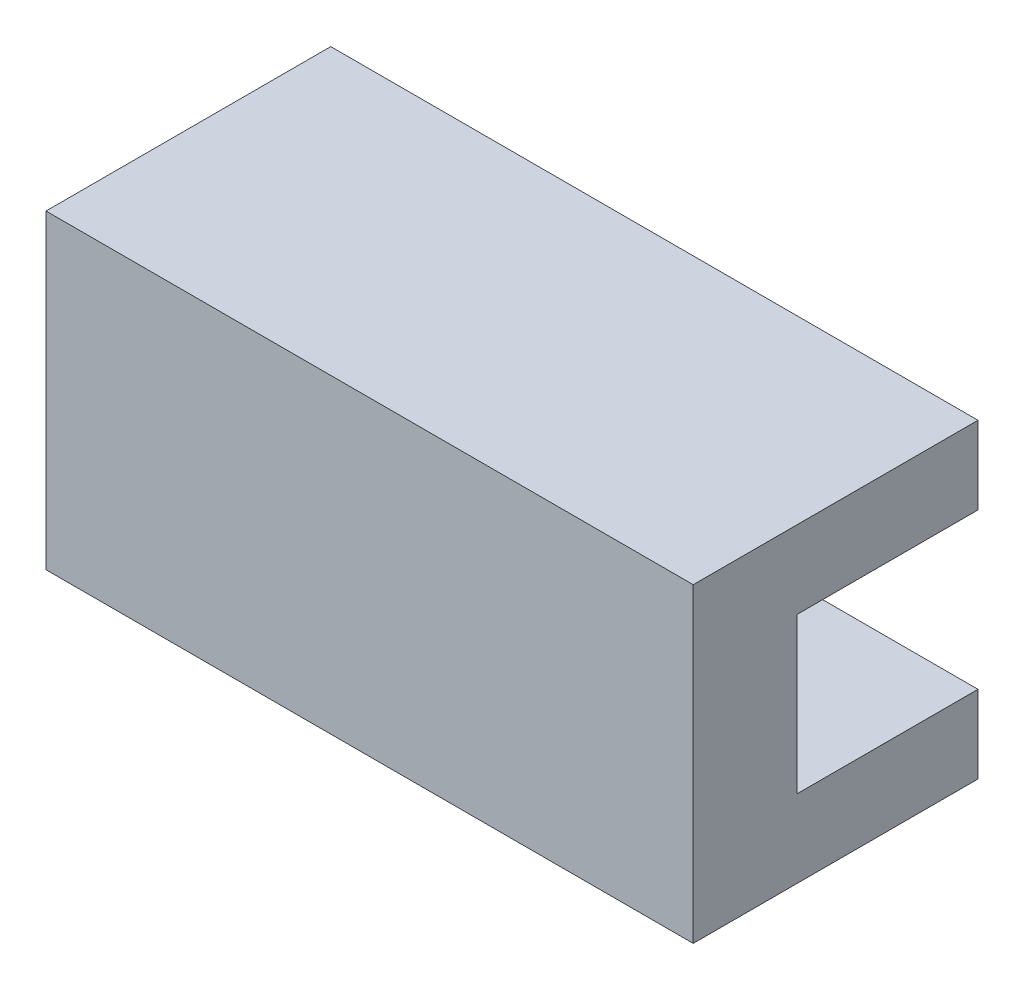
SolidWorks part; units mm, degrees
ref_plane "Front" through (0, 0, 0) normal (0, 0, 1) x (1, 0, 0)
ref_plane "Top" through (0, 0, 0) normal (0, 1, 0) x (1, 0, 0)
ref_plane "Right" through (0, 0, 0) normal (1, 0, 0) x (0, 0, -1)
sketch "Sketch1" plane through (0, 0, 0) normal (1, 0, 0) x (0, 0, -1)
  line L0 (24.8819, 19.6273) -> (2.8819, 19.6273)
  line L1 (2.8819, 19.6273) -> (2.8819, -4.3727)
  line L2 (2.8819, -4.3727) -> (24.8819, -4.3727)
  line L3 (24.8819, -4.3727) -> (24.8819, 1.6273)
  line L4 (24.8819, 1.6273) -> (10.8819, 1.6273)
  line L5 (10.8819, 1.6273) -> (10.8819, 13.6273)
  line L6 (10.8819, 13.6273) -> (24.8819, 13.6273)
  line L7 (24.8819, 13.6273) -> (24.8819, 19.6273)
  dimension "D1" = 14
  dimension "D2" = 22
  dimension "D3" = 6
  dimension "D4" = 12
  dimension "D5" = 22
  dimension "D6" = 24
extrude "Extrude1" add sketch "Sketch1" along normal blind 50
